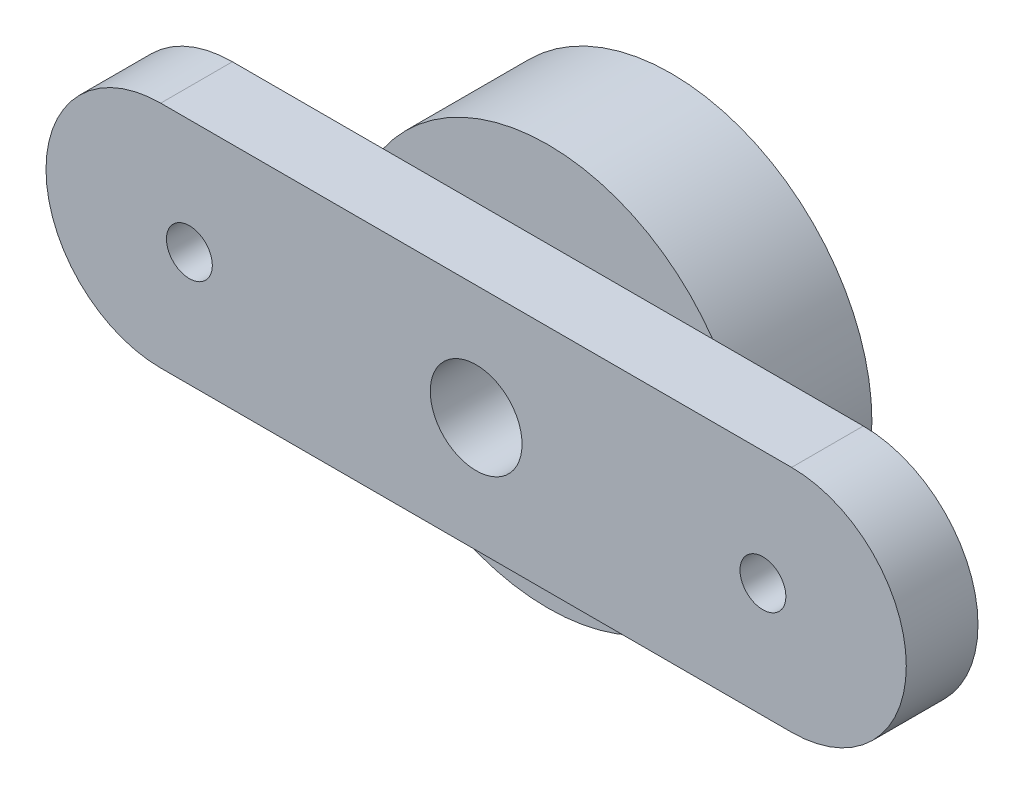
SolidWorks part; units mm, degrees
ref_plane "Front Plane" through (0, 0, 0) normal (0, 0, 1) x (1, 0, 0)
ref_plane "Top Plane" through (0, 0, 0) normal (0, 1, 0) x (1, 0, 0)
ref_plane "Right Plane" through (0, 0, 0) normal (1, 0, 0) x (0, 0, -1)
sketch "Sketch1" plane through (0, 0, 0) normal (0, 0, 1) x (1, 0, 0)
  circle A0 centre (0, 0) radius 7
  circle A1 centre (0, 0) radius 3.05
extrude "Hub" add sketch "Sketch1" along normal blind 4.3 from offset 2.2
sketch "Sketch2" plane through (0, 0, 0) normal (0, 0, 1) x (1, 0, 0)
  line L0 (-11, 4) -> (11, 4)
  line L1 (11, -4) -> (-11, -4)
  arc A0 (11, 4) -> (11, -4) centre (11, 0) cw
  arc A1 (-11, -4) -> (-11, 4) centre (-11, 0) cw
  circle A2 centre (0, 0) radius 1.6
  circle A3 centre (-10, 0) radius 0.8
  circle A4 centre (10, 0) radius 0.8
extrude "Arm" add sketch "Sketch2" along normal blind 2.5 from offset 6.5
